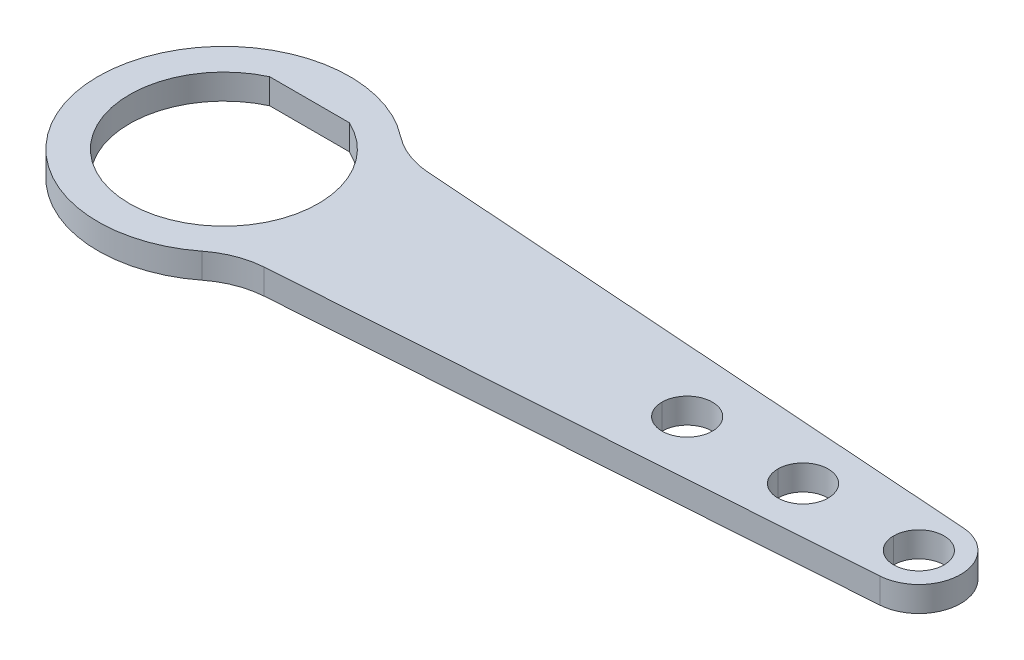
SolidWorks part; units mm, degrees
material "AISI 4130 Steel, annealed at 865C"
ref_plane "Front Plane" through (0, 0, 0) normal (0, 0, 1) x (1, 0, 0)
ref_plane "Top Plane" through (0, 0, 0) normal (0, 1, 0) x (1, 0, 0)
ref_plane "Right Plane" through (0, 0, 0) normal (1, 0, 0) x (0, 0, -1)
sketch "Sketch1" plane through (0, 0, 0) normal (0, 1, 0) x (1, 0, 0)
  line L3 (70.3988, 4.2087) -> (12.3315, 8.2754)
  line L4 (-55, 0) -> (55, 0) construction
  line L5 (70.3988, -4.2087) -> (12.3315, -8.2754)
  arc A2 (7.8186, -10.0079) -> (7.8186, 10.0079) centre (0, 0) cw
  arc A3 (70.3988, 4.2087) -> (70.3988, -4.2087) centre (70.104, 0) cw
  circle A4 centre (70.104, 0) radius 2.54
  circle A5 centre (58.42, 0) radius 2.54
  circle A6 centre (46.736, 0) radius 2.54
  arc A8 (12.3315, 8.2754) -> (7.8186, 10.0079) centre (12.9091, 16.5238) cw
  arc A9 (12.3315, -8.2754) -> (7.8186, -10.0079) centre (12.9091, -16.5238) ccw
  point P6 (9.4004, -8.5395)
  point P12 (15.0685, -6.002)
  point P13 (16.0289, 4.8487)
  point P17 (16.381, -6.2111)
  point P20 (9.2838, 8.6661)
  point P21 (17.7468, 6.2218)
  point P22 (17.7468, -6.7975)
  point P23 (17.7468, 6.566)
  point P24 (17.7468, -7.5612)
  point P25 (6.3312, -11.0094)
  point P26 (18.0197, -8.3652)
  point P27 (17.8434, 7.6845)
  point P28 (18.1079, -8.7532)
  point P29 (5.2837, -11.5487)
  point P30 (6.6522, 10.8184)
  point P31 (5.7097, -11.3441)
  point P32 (7.2701, 10.4132)
  point P33 (11.9038, -9.2343)
  point P34 (6.2656, -11.0468)
  point P35 (7.82, 10.0068)
  point P36 (12.3127, 8.0175)
  point P37 (0, 0)
  point P38 (0, 0)
  point P41 (8.2603, 9.6466)
  point P42 (0, 0)
  point P43 (0, 0)
  point P44 (71.639, -3.9819)
  point P45 (12.3315, 8.2754)
  dimension "D1" = 5.08
  dimension "D3" = 12.7
  dimension "D4" = 5.08
  dimension "D5" = 46.736
  dimension "D2" = 58.42
  dimension "D6" = 70.104
sketch "Sketch3" plane through (0, 0, 0) normal (0, 1, 0) x (1, 0, 0)
  line L0 (-4.0181, 8.636) -> (4.0181, 8.636)
  arc A0 (4.0181, 8.636) -> (-4.0181, 8.636) centre (0, 0) cw
  point P3 (0, 8.636)
  point P4 (0.6242, 0.3427)
  point P5 (0.5262, 0.2413)
  point P6 (0.2934, 0.1889)
  point P7 (0, 0)
  point P8 (0, 0)
extrude "Boss-Extrude1" add sketch "Sketch1" along normal blind 2.54
extrude "Cut-Extrude1" cut sketch "Sketch3" against normal through all both and the other way through all
sketch "Sketch6" plane through (0, 0, 0) normal (0, -1, 0) x (1, 0, 0)
  line L0 (44.196, 0) -> (49.276, 0)
  line L1 (55.88, 0) -> (60.96, 0)
  line L2 (67.564, 0) -> (72.644, 0)
  circle A0 centre (46.736, 0) radius 2.54 construction
  circle A1 centre (58.42, 0) radius 2.54 construction
  circle A2 centre (70.104, 0) radius 2.54 construction
  point P15 (0, 0)
split line "Split Line1"
